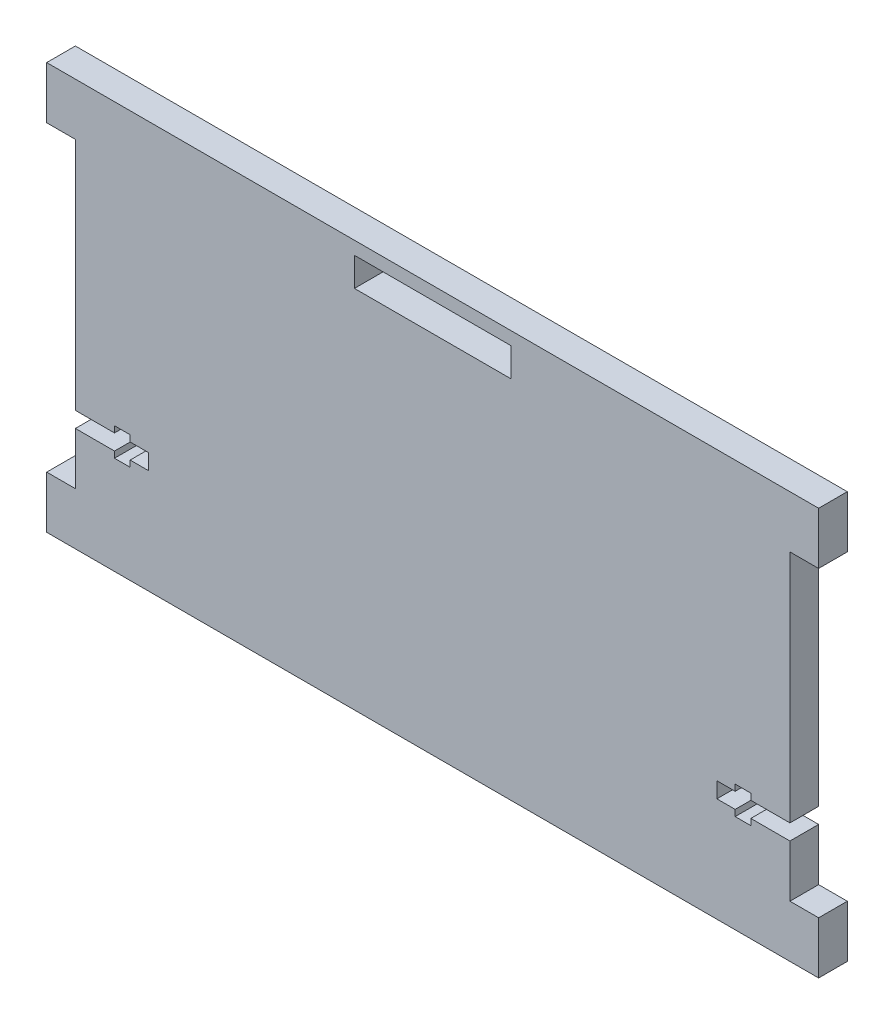
SolidWorks part; units mm, degrees
ref_plane "Front Plane" through (0, 0, 0) normal (0, 0, 1) x (1, 0, 0)
ref_plane "Top Plane" through (0, 0, 0) normal (0, 1, 0) x (1, 0, 0)
ref_plane "Right Plane" through (0, 0, 0) normal (1, 0, 0) x (0, 0, -1)
sketch "Sketch1" plane through (0, 0, 0) normal (0, 0, 1) x (1, 0, 0)
  line L0 (0, 23) -> (0, 68)
  line L1 (0, 0) -> (137, 0)
  line L2 (0, 10) -> (0, 20)
  line L3 (0, 78) -> (137, 78)
  line L4 (137, 10) -> (137, 20)
  line L5 (53.5, 75.5) -> (83.5, 75.5)
  line L6 (53.5, 75.5) -> (53.5, 70)
  line L7 (53.5, 70) -> (83.5, 70)
  line L8 (83.5, 75.5) -> (83.5, 70)
  line L9 (0, 78) -> (-5.5, 78)
  line L10 (0, 20) -> (7.5, 20)
  line L11 (0, 68) -> (-5.5, 68)
  line L12 (-5.5, 78) -> (-5.5, 68)
  line L13 (0, 0) -> (-5.5, 0)
  line L14 (137, 23) -> (137, 68)
  line L15 (0, 10) -> (-5.5, 10)
  line L16 (-5.5, 0) -> (-5.5, 10)
  line L17 (137, 78) -> (142.5, 78)
  line L18 (0, 23) -> (7.5, 23)
  line L19 (137, 68) -> (142.5, 68)
  line L20 (142.5, 78) -> (142.5, 68)
  line L21 (137, 0) -> (142.5, 0)
  line L22 (14, 20) -> (14, 23)
  line L23 (137, 10) -> (142.5, 10)
  line L24 (142.5, 0) -> (142.5, 10)
  line L25 (7.5, 24.2) -> (10.5, 24.2)
  line L26 (7.5, 24.2) -> (7.5, 23)
  line L27 (7.5, 18.8) -> (10.5, 18.8)
  line L28 (10.5, 24.2) -> (10.5, 23)
  line L29 (7.5, 20) -> (7.5, 18.8)
  line L30 (10.5, 23) -> (14, 23)
  line L31 (10.5, 20) -> (10.5, 18.8)
  line L32 (10.5, 20) -> (14, 20)
  line L33 (129.5, 20) -> (129.5, 18.8)
  line L34 (137, 20) -> (129.5, 20)
  line L36 (137, 23) -> (129.5, 23)
  line L37 (123, 20) -> (123, 23)
  line L38 (126.5, 24.2) -> (129.5, 24.2)
  line L39 (126.5, 24.2) -> (126.5, 23)
  line L40 (126.5, 18.8) -> (129.5, 18.8)
  line L41 (129.5, 24.2) -> (129.5, 23)
  line L42 (126.5, 20) -> (126.5, 18.8)
  line L43 (126.5, 23) -> (123, 23)
  line L44 (126.5, 20) -> (123, 20)
  dimension "D1" = 137
  dimension "D2" = 78
  dimension "D3" = 5.5
  dimension "D4" = 2.5
  dimension "D5" = 30
  dimension "D6" = 53.5
  dimension "D7" = 5.5
  dimension "D8" = 5.5
  dimension "D9" = 10
  dimension "D10" = 10
  dimension "D11" = 10
  dimension "D12" = 10
  dimension "D13" = 5.5
  dimension "D14" = 5.5
  dimension "D15" = 10
  dimension "D16" = 3
  dimension "D17" = 14
  dimension "D18" = 1.2
  dimension "D19" = 5.4
  dimension "D20" = 3
  dimension "D21" = 7.5
  dimension "D22" = 3
  dimension "D23" = 10
  dimension "D24" = 14
  dimension "D25" = 7.5
  dimension "D26" = 3
  dimension "D27" = 1.2
  dimension "D28" = 5.4
extrude "Boss-Extrude1" add sketch "Sketch1" along normal blind 5.5
